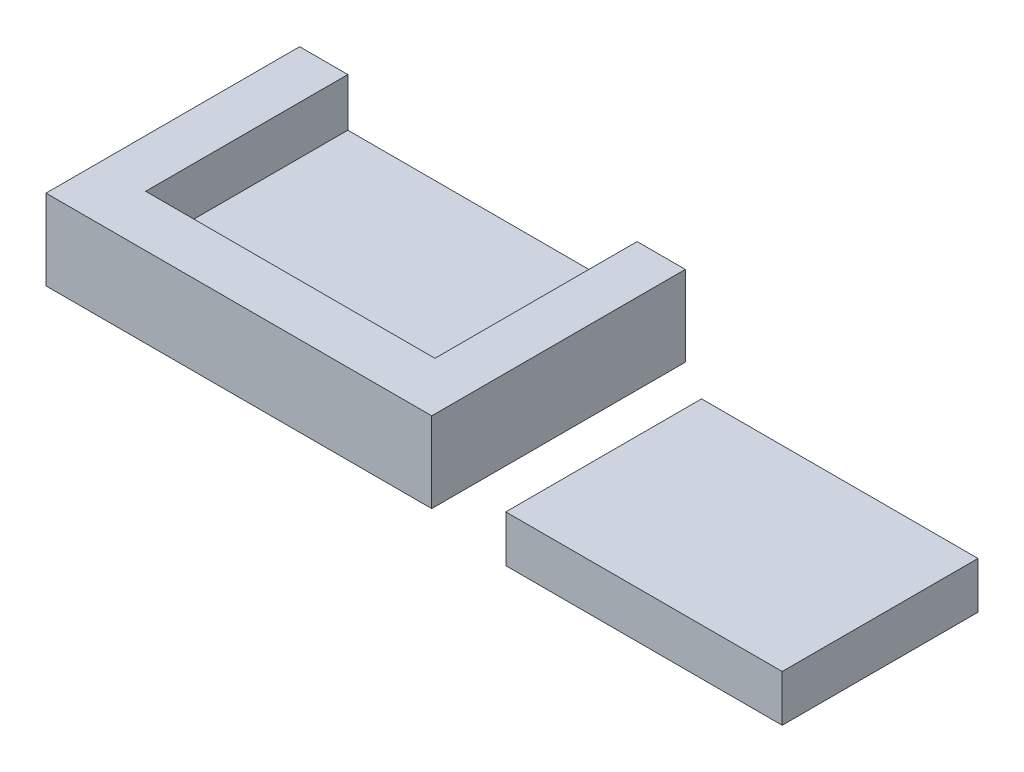
SolidWorks part; units mm, degrees
ref_plane "Front Plane" through (0, 0, 0) normal (0, 0, 1) x (1, 0, 0)
ref_plane "Top Plane" through (0, 0, 0) normal (0, 1, 0) x (1, 0, 0)
ref_plane "Right Plane" through (0, 0, 0) normal (1, 0, 0) x (0, 0, -1)
sketch "Sketch1" plane through (0, 0, 0) normal (0, 1, 0) x (1, 0, 0)
  line L1 (0, 0) -> (24, 0)
  line L2 (0, 0) -> (0, 15.78)
  line L3 (0, 15.78) -> (24, 15.78)
  line L4 (24, 0) -> (24, 15.78)
  dimension "D1" = 24
  dimension "D2" = 15.78
extrude "Boss-Extrude1" add sketch "Sketch1" along normal blind 5
sketch "Sketch2" plane through (0, 5, 0) normal (0, 1, 0) x (1, 0, 0)
  line L0 (24, 15.78) -> (0, 15.78) construction
  line L1 (3, 15.78) -> (21, 15.78)
  line L2 (3, 15.78) -> (3, 3.2)
  line L3 (3, 3.2) -> (21, 3.2)
  line L4 (21, 15.78) -> (21, 3.2)
  line L5 (0, 15.78) -> (0, 0) construction
  dimension "D1" = 18
  dimension "D2" = 12.58
  dimension "D3" = 3
extrude "Cut-Extrude1" cut sketch "Sketch2" against normal blind 3
sketch "Sketch3" plane through (0, 0, 0) normal (0, 1, 0) x (1, 0, 0)
  line L1 (29.3796, -0.7725) -> (46.5796, -0.7725)
  line L2 (29.3796, -0.7725) -> (29.3796, 11.4095)
  line L3 (29.3796, 11.4095) -> (46.5796, 11.4095)
  line L4 (46.5796, -0.7725) -> (46.5796, 11.4095)
  dimension "D1" = 17.2
  dimension "D2" = 12.182
extrude "Boss-Extrude2" add sketch "Sketch3" along normal blind 2.9 separate body
